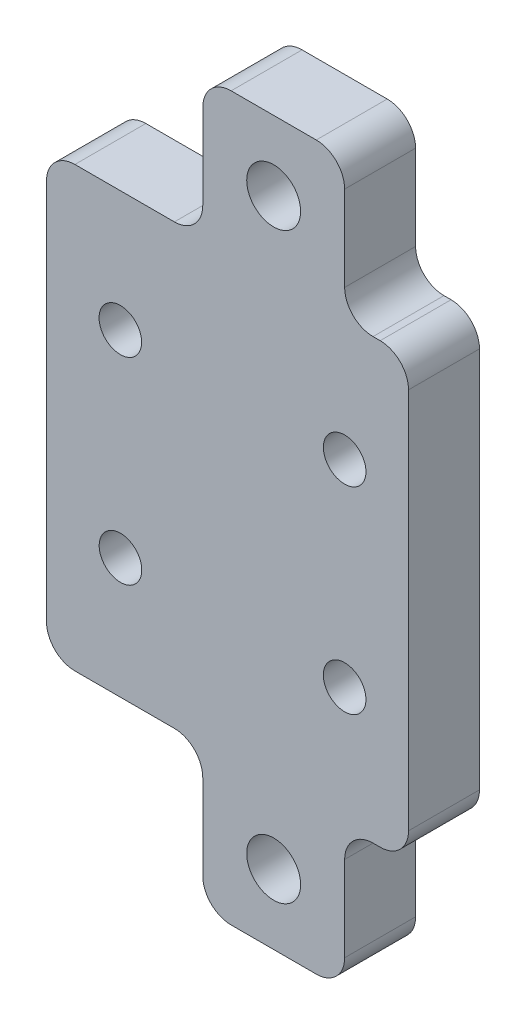
SolidWorks part; units mm, degrees
ref_plane "Front Plane" through (0, 0, 0) normal (0, 0, 1) x (1, 0, 0)
ref_plane "Top Plane" through (0, 0, 0) normal (0, 1, 0) x (1, 0, 0)
ref_plane "Right Plane" through (0, 0, 0) normal (1, 0, 0) x (0, 0, -1)
sketch "Sketch1" plane through (0, 0, 0) normal (0, 0, 1) x (1, 0, 0)
  line L0 (-6.9973, -256.787) -> (-14.0085, -256.787)
  line L1 (7.5051, -225.8705) -> (7.0027, -225.8705)
  line L2 (9.5051, -227.8705) -> (9.5051, -254.787)
  line L3 (7.5051, -256.787) -> (7.0027, -256.787)
  line L4 (-16.0085, -227.8705) -> (-16.0085, -254.787)
  line L6 (-4.9973, -258.787) -> (-4.9973, -264.787)
  line L7 (-2.9973, -266.787) -> (3.0027, -266.787)
  line L8 (5.0027, -258.787) -> (5.0027, -264.787)
  line L9 (-16.0085, -241.3288) -> (-11.4863, -241.3288) construction
  line L10 (5.0027, -223.8705) -> (5.0027, -217.8705)
  line L11 (-2.9973, -215.8705) -> (3.0027, -215.8705)
  line L12 (-4.9973, -223.8705) -> (-4.9973, -217.8705)
  line L13 (-6.9973, -225.8705) -> (-14.0085, -225.8705)
  circle A0 centre (0, -261.8761) radius 1.9
  arc A1 (-4.9973, -264.787) -> (-2.9973, -266.787) centre (-2.9973, -264.787) ccw
  arc A2 (3.0027, -266.787) -> (5.0027, -264.787) centre (3.0027, -264.787) ccw
  arc A3 (7.0027, -256.787) -> (5.0027, -258.787) centre (7.0027, -258.787) ccw
  circle A4 centre (5.0027, -234.3751) radius 1.5008
  circle A5 centre (-10.8058, -234.3751) radius 1.5008
  arc A8 (-6.9973, -256.787) -> (-4.9973, -258.787) centre (-6.9973, -258.787) cw
  arc A9 (7.5051, -225.8705) -> (9.5051, -227.8705) centre (7.5051, -227.8705) cw
  arc A10 (9.5051, -254.787) -> (7.5051, -256.787) centre (7.5051, -254.787) cw
  arc A11 (-14.0085, -225.8705) -> (-16.0085, -227.8705) centre (-14.0085, -227.8705) ccw
  arc A12 (-14.0085, -256.787) -> (-16.0085, -254.787) centre (-14.0085, -254.787) cw
  arc A13 (-6.9973, -225.8705) -> (-4.9973, -223.8705) centre (-6.9973, -223.8705) ccw
  arc A14 (7.0027, -225.8705) -> (5.0027, -223.8705) centre (7.0027, -223.8705) cw
  arc A15 (3.0027, -215.8705) -> (5.0027, -217.8705) centre (3.0027, -217.8705) cw
  arc A16 (-4.9973, -217.8705) -> (-2.9973, -215.8705) centre (-2.9973, -217.8705) cw
  circle A17 centre (0, -220.7815) radius 1.9
  circle A20 centre (5.0027, -248.2751) radius 1.5
  circle A21 centre (-10.7973, -248.2751) radius 1.5
  point P27 (-4.9973, -256.787)
  point P51 (-4.9973, -225.8705)
  point P52 (0, 0)
  point P53 (0, 0)
  point P55 (0, 0)
  dimension "D3" = 3.8
  dimension "D4" = 2
  dimension "D5" = 2
  dimension "D6" = 2
  dimension "D1" = 10
  dimension "D2" = 10
extrude "Boss-Extrude1" add sketch "Sketch1" along normal blind 5
